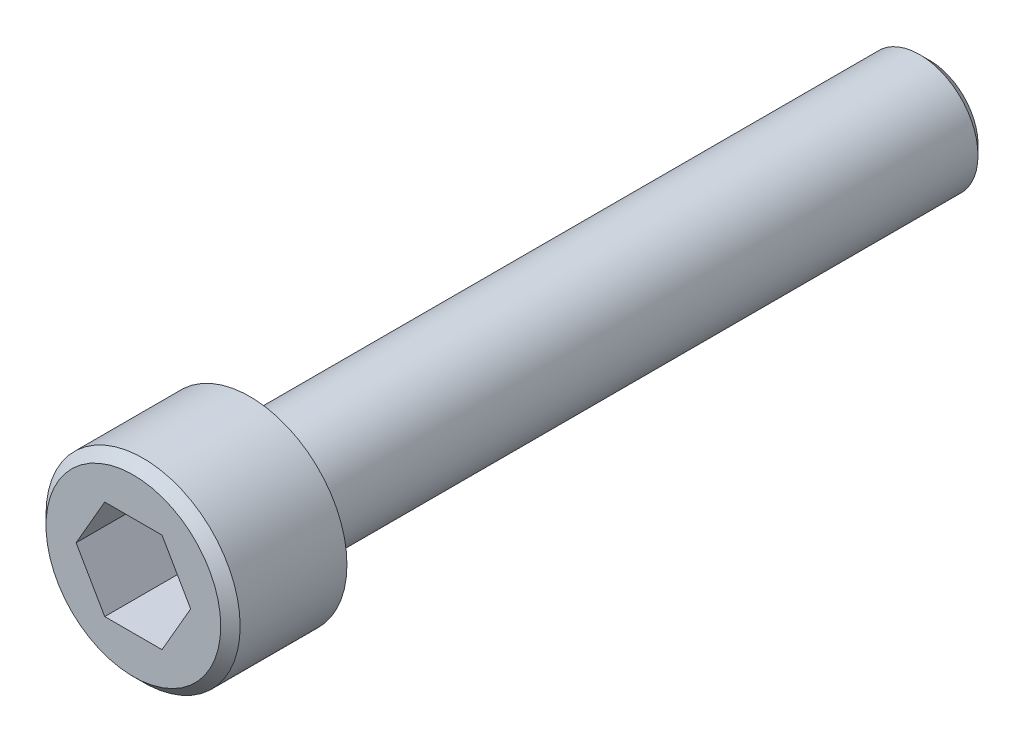
SolidWorks part; units mm, degrees
ref_plane "Alzado" through (0, 0, 0) normal (0, 0, 1) x (1, 0, 0)
ref_plane "Planta" through (0, 0, 0) normal (0, 1, 0) x (1, 0, 0)
ref_plane "Vista lateral" through (0, 0, 0) normal (1, 0, 0) x (0, 0, -1)
sketch "Croquis1" plane through (0, 0, 0) normal (0, 0, 1) x (1, 0, 0)
  circle A0 centre (0, 0) radius 5
  dimension "D1" = 10
extrude "Saliente-Extruir1" add sketch "Croquis1" along normal blind 6
sketch "Croquis2" plane through (0, 0, 0) normal (0, 0, -1) x (-1, 0, 0)
  circle A0 centre (0, 0) radius 3
  dimension "D1" = 6
extrude "Saliente-Extruir2" add sketch "Croquis2" along normal blind 35
chamfer "Chaflán1" distance 0.5 angle 45 2 edges at (5, 0, 6) (-3, 0, -35)
sketch "Croquis3" plane through (0, 0, 6) normal (0, 0, 1) x (1, 0, 0)
  line L1 (2.95, 0) -> (1.475, 2.5548)
  line L2 (1.475, 2.5548) -> (-1.475, 2.5548)
  line L3 (-1.475, 2.5548) -> (-2.95, 0)
  line L4 (-2.95, 0) -> (-1.475, -2.5548)
  line L5 (-1.475, -2.5548) -> (1.475, -2.5548)
  line L6 (1.475, -2.5548) -> (2.95, 0)
  circle A0 centre (0, 0) radius 2.5548 construction
  dimension "D1" = 5.9
extrude "Cortar-Extruir1" cut sketch "Croquis3" against normal blind 4
